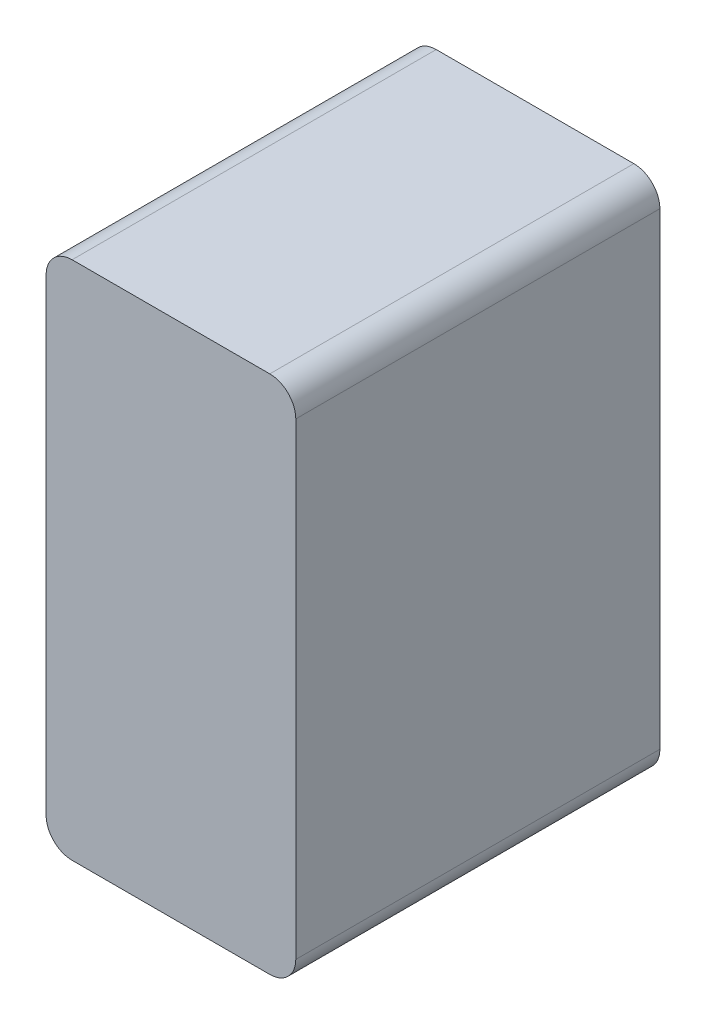
SolidWorks part; units mm, degrees
ref_plane "前视基准面" through (0, 0, 0) normal (0, 0, 1) x (1, 0, 0)
ref_plane "上视基准面" through (0, 0, 0) normal (0, 1, 0) x (1, 0, 0)
ref_plane "右视基准面" through (0, 0, 0) normal (1, 0, 0) x (0, 0, -1)
other "Configuration Table"
sketch "草图1" plane through (0, 0, 0) normal (0, 0, 1) x (1, 0, 0)
  line L1 (-24, 50) -> (24, 50)
  line L2 (-24, 50) -> (-24, -50)
  line L3 (-24, -50) -> (24, -50)
  line L4 (24, 50) -> (24, -50)
  line L5 (-24, 50) -> (24, -50) construction
  line L6 (-24, -50) -> (24, 50) construction
  point P1 (0, 0)
  dimension "D1" = 100
  dimension "D2" = 48
extrude "凸台-拉伸1" add sketch "草图1" along normal blind 70
sketch "草图2" plane through (0, 0, 0) normal (0, 0, -1) x (-1, 0, 0)
  line L1 (-22, 48) -> (22, 48)
  line L2 (-22, 48) -> (-22, -48)
  line L3 (-22, -48) -> (22, -48)
  line L4 (22, 48) -> (22, -48)
  line L5 (-22, 48) -> (22, -48) construction
  line L6 (-22, -48) -> (22, 48) construction
  point P0 (0, 0)
  dimension "D1" = 44
  dimension "D2" = 96
extrude "切除-拉伸1" cut sketch "草图2" against normal blind 68
fillet "圆角1" radius 5 8 edges at (-24, -50, 35) (24, -50, 35) (-24, 50, 35) (24, 50, 35) (-22, 48, 34) (22, 48, 34) (-22, -48, 34) (22, -48, 34)
